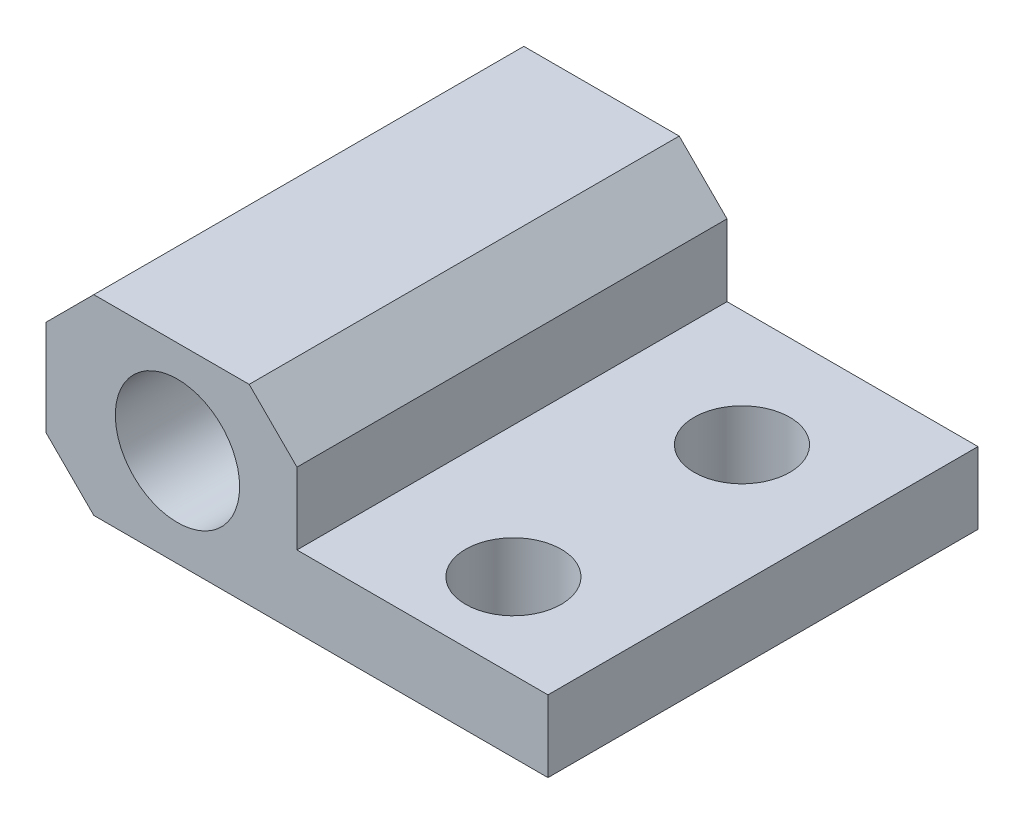
SolidWorks part; units mm, degrees
ref_plane "Спереди" through (0, 0, 0) normal (0, 0, 1) x (1, 0, 0)
ref_plane "Сверху" through (0, 0, 0) normal (0, 1, 0) x (1, 0, 0)
ref_plane "Справа" through (0, 0, 0) normal (1, 0, 0) x (0, 0, -1)
sketch "Эскиз1" plane through (0, 0, 0) normal (0, 1, 0) x (1, 0, 0)
  line L0 (10, -17.9909) -> (0, -17.9909) construction
  line L1 (-11, 0) -> (10, 0)
  line L2 (-11, 0) -> (-11, -17.9909)
  line L3 (-11, -17.9909) -> (10, -17.9909)
  line L4 (10, 0) -> (10, -17.9909)
extrude "Вытянуть1" add sketch "Эскиз1" along normal blind 8
sketch "Эскиз2" plane through (0, 8, 0) normal (0, 1, 0) x (1, 0, 0)
  line L0 (-11, -17.9909) -> (10, -17.9909) construction
  line L1 (-0.5, -17.9909) -> (10, -17.9909)
  line L2 (-0.5, -17.9909) -> (-0.5, 0.0035)
  line L3 (-0.5, 0.0035) -> (10, 0.0035)
  line L4 (10, -17.9909) -> (10, 0.0035)
extrude "Вырез-Вытянуть1" cut sketch "Эскиз2" against normal blind 5
sketch "Эскиз3" plane through (0, 3, 0) normal (0, 1, 0) x (1, 0, 0)
  circle A0 centre (5, -14.4361) radius 2
  circle A1 centre (5, -4.8736) radius 2
extrude "Вырез-Вытянуть2" cut sketch "Эскиз3" against normal through all
sketch "Эскиз4" plane through (0, 0, 17.9909) normal (0, 0, 1) x (1, 0, 0)
  circle A0 centre (-5.5, 4.0907) radius 2.6
extrude "Вырез-Вытянуть3" cut sketch "Эскиз4" against normal blind 15
chamfer "Фаска1" distance 2 angle 45 3 edges at (-0.5, 8, 8.9954) (-11, 0, 8.9954) (-11, 8, 8.9954)
